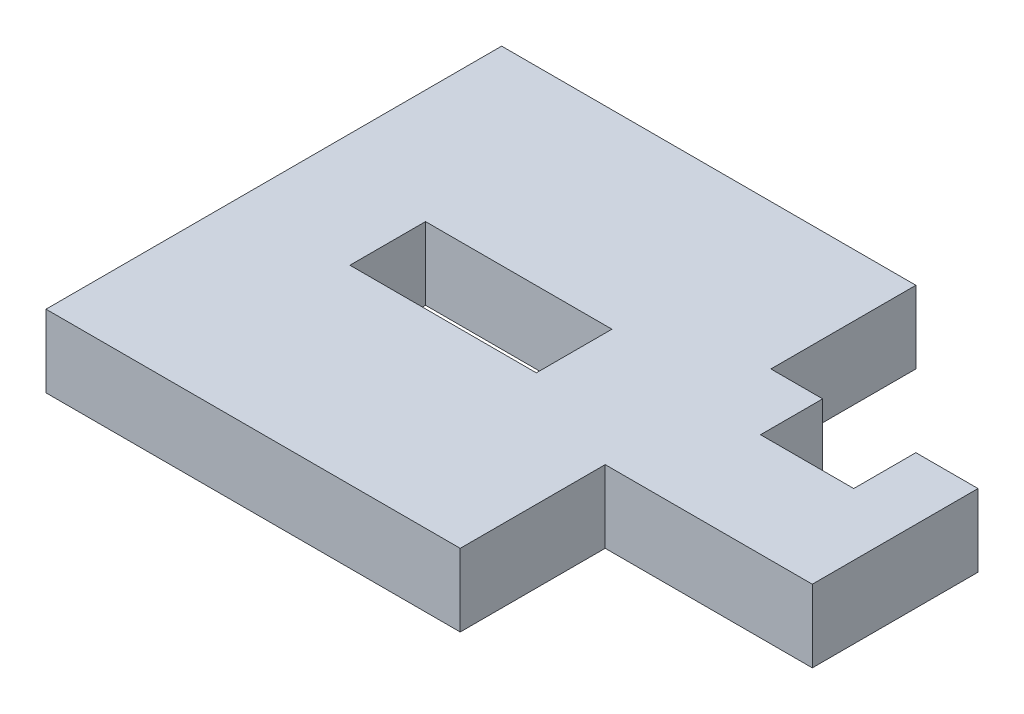
SolidWorks part; units mm, degrees
ref_plane "Front Plane" through (0, 0, 0) normal (0, 0, 1) x (1, 0, 0)
ref_plane "Top Plane" through (0, 0, 0) normal (0, 1, 0) x (1, 0, 0)
ref_plane "Right Plane" through (0, 0, 0) normal (1, 0, 0) x (0, 0, -1)
sketch "Sketch1" plane through (0, 0, 0) normal (0, 1, 0) x (1, 0, 0)
  line L1 (-10, 11) -> (10, 11)
  line L2 (-10, 11) -> (-10, -11)
  line L3 (-10, -11) -> (10, -11)
  line L4 (10, 11) -> (10, -11)
  line L6 (4.5, -1.825) -> (-4.5, -1.825)
  line L7 (4.5, -1.825) -> (4.5, 1.825)
  line L8 (4.5, 1.825) -> (-4.5, 1.825)
  line L9 (-4.5, -1.825) -> (-4.5, 1.825)
  point P4 (0, 1.825)
  point P10 (0, 11)
  point P11 (-4.5, 0)
  point P12 (-10, 0)
  dimension "D1" = 9
  dimension "D2" = 3.65
  dimension "D3" = 20
  dimension "D4" = 22
extrude "Boss-Extrude1" add sketch "Sketch1" along normal blind 4
sketch "Sketch2" plane through (0, 0, 0) normal (0, 1, 0) x (1, 0, 0)
  line L0 (10, 4) -> (20, 4)
  line L1 (10, -11) -> (10, 11) construction
  line L2 (20, 4) -> (20, -4)
  line L3 (20, -4) -> (10, -4)
  line L4 (10, 4) -> (10, -4)
  point P6 (10, 0)
  point P7 (20, 0)
  dimension "D1" = 8
  dimension "D2" = 10
extrude "Boss-Extrude3" add sketch "Sketch2" along normal blind 4
sketch "Sketch3" plane through (0, 0, 0) normal (0, 1, 0) x (1, 0, 0)
  line L0 (10, 4) -> (10, 11) construction
  line L1 (12.5, 4) -> (17, 4)
  line L2 (12.5, 4) -> (12.5, 1)
  line L3 (12.5, 1) -> (17, 1)
  line L4 (17, 4) -> (17, 1)
  dimension "D1" = 4.5
  dimension "D2" = 3
  dimension "D3" = 2.5
extrude "Cut-Extrude1" cut sketch "Sketch3" along normal through all
chamfer "Chamfer1" distance 0.5 angle 45 16 edges at (0, 0, -11) (-10, 0, 0) (0, 0, 11) (10, 0, 7.5) (15, 0, 4) (20, 0, 0) (18.5, 0, -4) (17, 0, -2.5) (14.75, 0, -1) (10, 0, -7.5) (0, 0, 1.825) (-4.5, 0, 0) (0, 0, -1.825) (4.5, 0, 0) (11.25, 0, -4) (12.5, 0, -2.5)
